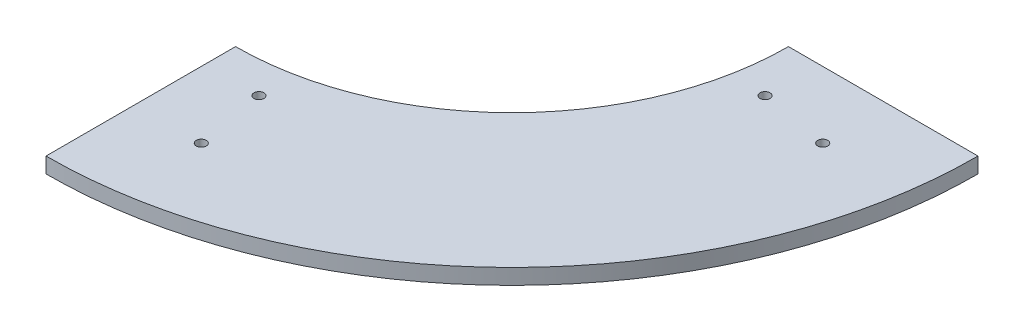
SolidWorks part; units mm, degrees
ref_plane "Front Plane" through (0, 0, 0) normal (0, 0, 1) x (1, 0, 0)
ref_plane "Top Plane" through (0, 0, 0) normal (0, 1, 0) x (1, 0, 0)
ref_plane "Right Plane" through (0, 0, 0) normal (1, 0, 0) x (0, 0, -1)
sketch "Sketch1" plane through (0, 0, 0) normal (0, 1, 0) x (1, 0, 0)
  line L0 (111.125, 0) -> (187.325, 0)
  line L1 (0, -111.125) -> (0, -187.325)
  arc A0 (0, -187.325) -> (187.325, 0) centre (0, 0) ccw
  arc A1 (0, -111.125) -> (111.125, 0) centre (0, 0) ccw
  dimension "D1" = 222.25
  dimension "D2" = 76.2
extrude "Boss-Extrude1" add sketch "Sketch1" along normal blind 6.25
sketch "Sketch2" plane through (0, 6.25, 0) normal (0, 1, 0) x (1, 0, 0)
  line L0 (0, 0) -> (0, -187.325) construction
  line L1 (0, 0) -> (187.325, 0) construction
  line L2 (0, 0) -> (132.4588, -132.4588) construction
  line L3 (0, 0) -> (32.5286, -184.4791) construction
  line L4 (0, 0) -> (184.4791, -32.5286) construction
  arc A0 (0, -187.325) -> (187.325, 0) centre (0, 0) ccw construction
  circle A4 centre (21.7777, -123.5072) radius 2
  arc A5 (0, -125.4125) -> (125.4125, 0) centre (0, 0) ccw
  arc A6 (0, -125.4125) -> (125.4125, 0) centre (0, 0) ccw construction
  circle A7 centre (123.5072, -21.7777) radius 2
  arc A8 (0, -153.9875) -> (153.9875, 0) centre (0, 0) ccw construction
  circle A9 centre (26.7396, -151.6481) radius 2
  circle A10 centre (151.6481, -26.7396) radius 2
  dimension "D2" = 14.2875
  dimension "D3" = 4
  dimension "D5" = 4
  dimension "D1" = 10
  dimension "D4" = 28.575
extrude "Cut-Extrude1" cut sketch "Sketch2" against normal blind 6.35
